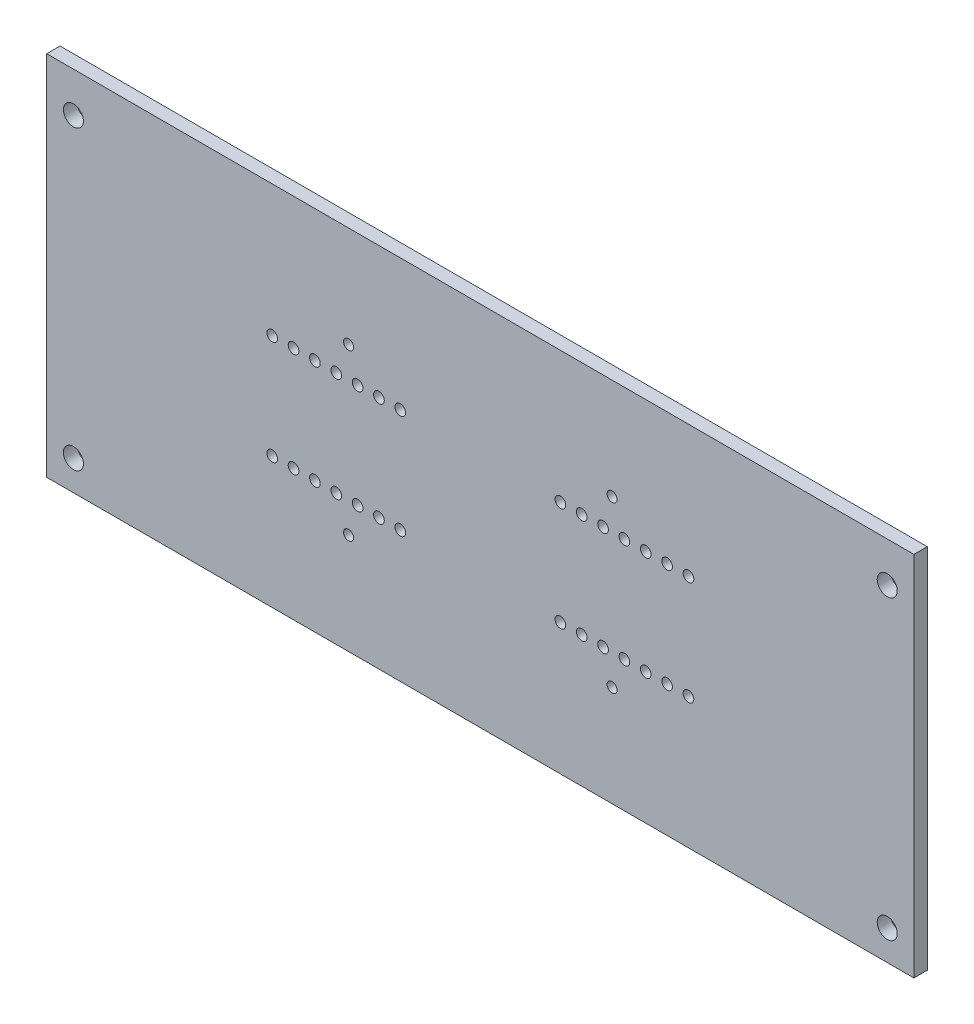
SolidWorks part; units mm, degrees
ref_plane "Front Plane" through (0, 0, 0) normal (0, 0, 1) x (1, 0, 0)
ref_plane "Top Plane" through (0, 0, 0) normal (0, 1, 0) x (1, 0, 0)
ref_plane "Right Plane" through (0, 0, 0) normal (1, 0, 0) x (0, 0, -1)
sketch "Sketch1" plane through (0, 0, 0) normal (0, 0, 1) x (1, 0, 0)
  line L1 (130, 55) -> (-130, 55)
  line L2 (130, 55) -> (130, -55)
  line L3 (130, -55) -> (-130, -55)
  line L4 (-130, 55) -> (-130, -55)
  line L5 (130, 55) -> (-130, -55) construction
  line L6 (130, -55) -> (-130, 55) construction
  point P0 (0, 0)
  dimension "D1" = 260
  dimension "D2" = 110
extrude "Boss-Extrude1" add sketch "Sketch1" along normal blind 4
sketch "Sketch2" plane through (0, 0, 0) normal (0, 0, -1) x (-1, 0, 0)
  circle A0 centre (-122, 43) radius 3
  circle A1 centre (122, 43) radius 3
  circle A4 centre (75, 43) radius 3 construction
  circle A5 centre (122, -46) radius 3 construction
  circle A6 centre (-75, 43) radius 3 construction
  circle A7 centre (-122, -46) radius 3 construction
  circle A8 centre (75, 43) radius 3
  circle A9 centre (122, -46) radius 3
  circle A10 centre (-75, 43) radius 3
  circle A11 centre (-122, -46) radius 3
  point P16 (0, 0)
  point P17 (0, 0)
  point P18 (0, 0)
  point P19 (0, 0)
  point P20 (0, 0)
  dimension "D1" = 6
  dimension "D2" = 6
extrude "Cut-Extrude1" cut sketch "Sketch2" against normal through all
sketch "Sketch5" plane through (0, 0, 4) normal (0, 0, 1) x (1, 0, 0)
  circle A4 centre (-39.5, 24.75) radius 1.5 construction
  circle A5 centre (39.5, 24.75) radius 1.5 construction
  circle A6 centre (39.5, -24.75) radius 1.5 construction
  circle A7 centre (-39.5, -24.75) radius 1.5 construction
  circle A8 centre (-39.5, 24.75) radius 1.5
  circle A9 centre (39.5, 24.75) radius 1.5
  circle A10 centre (39.5, -24.75) radius 1.5
  circle A11 centre (-39.5, -24.75) radius 1.5
extrude "Cut-Extrude3" cut sketch "Sketch5" against normal through all
sketch "Sketch6" plane through (0, 0, 4) normal (0, 0, 1) x (1, 0, 0)
  line L0 (0, 0) -> (0, -55) construction
  line L1 (-130, -55) -> (130, -55) construction
  circle A0 centre (-24, 15.5494) radius 1.6 construction
  circle A1 centre (-30.4, 15.5494) radius 1.6 construction
  circle A2 centre (-36.8, 15.5494) radius 1.6 construction
  circle A3 centre (-43.2, 15.5494) radius 1.6 construction
  circle A4 centre (-49.6, 15.5494) radius 1.6 construction
  circle A5 centre (-56, 15.5494) radius 1.6 construction
  circle A6 centre (-62.4, 15.5494) radius 1.6 construction
  circle A7 centre (-62.4, -15.6506) radius 1.6 construction
  circle A8 centre (-56, -15.6506) radius 1.6 construction
  circle A9 centre (-49.6, -15.6506) radius 1.6 construction
  circle A10 centre (-43.2, -15.6506) radius 1.6 construction
  circle A11 centre (-36.8, -15.6506) radius 1.6 construction
  circle A12 centre (-30.4, -15.6506) radius 1.6 construction
  circle A13 centre (-24, -15.6506) radius 1.6 construction
  circle A14 centre (-24, 15.5494) radius 1.6
  circle A15 centre (-30.4, 15.5494) radius 1.6
  circle A16 centre (-36.8, 15.5494) radius 1.6
  circle A17 centre (-43.2, 15.5494) radius 1.6
  circle A18 centre (-49.6, 15.5494) radius 1.6
  circle A19 centre (-56, 15.5494) radius 1.6
  circle A20 centre (-62.4, 15.5494) radius 1.6
  circle A21 centre (-62.4, -15.6506) radius 1.6
  circle A22 centre (-56, -15.6506) radius 1.6
  circle A23 centre (-49.6, -15.6506) radius 1.6
  circle A24 centre (-43.2, -15.6506) radius 1.6
  circle A25 centre (-36.8, -15.6506) radius 1.6
  circle A26 centre (-30.4, -15.6506) radius 1.6
  circle A27 centre (-24, -15.6506) radius 1.6
  circle A28 centre (24, -15.6506) radius 1.6
  circle A29 centre (30.4, -15.6506) radius 1.6
  circle A30 centre (36.8, -15.6506) radius 1.6
  circle A31 centre (43.2, -15.6506) radius 1.6
  circle A32 centre (49.6, -15.6506) radius 1.6
  circle A33 centre (56, -15.6506) radius 1.6
  circle A34 centre (62.4, -15.6506) radius 1.6
  circle A35 centre (62.4, 15.5494) radius 1.6
  circle A36 centre (56, 15.5494) radius 1.6
  circle A37 centre (49.6, 15.5494) radius 1.6
  circle A38 centre (43.2, 15.5494) radius 1.6
  circle A39 centre (36.8, 15.5494) radius 1.6
  circle A40 centre (30.4, 15.5494) radius 1.6
  circle A41 centre (24, 15.5494) radius 1.6
extrude "Cut-Extrude4" cut sketch "Sketch6" against normal through all
sketch "Sketch7" plane through (0, 0, 0) normal (0, 0, -1) x (-1, 0, 0)
  circle A0 centre (75, 43) radius 3 construction
  circle A1 centre (-75, 43) radius 3 construction
  circle A2 centre (75, 43) radius 3
  circle A3 centre (-75, 43) radius 3
extrude "Boss-Extrude2" add sketch "Sketch7" against normal up to surface (4 mm away) up to face at (-28.8, 15.5494, 4)
